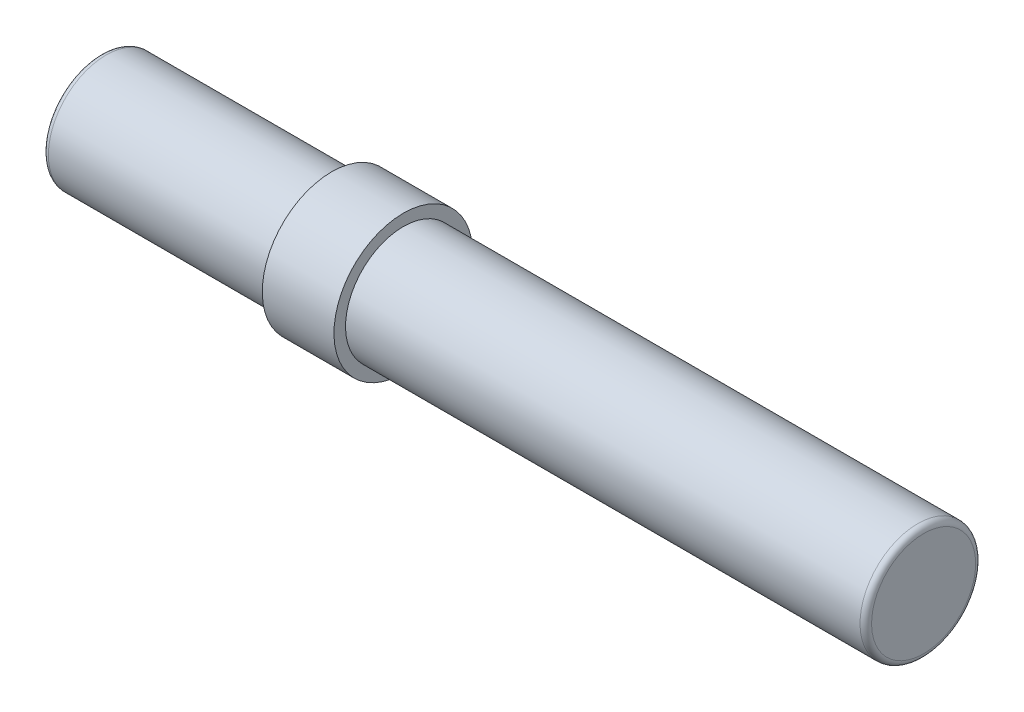
SolidWorks part; units mm, degrees
material "1.5714 (16NiCr4)"
ref_plane "Ebene vorne" through (0, 0, 0) normal (0, 0, 1) x (1, 0, 0)
ref_plane "Ebene oben" through (0, 0, 0) normal (0, 1, 0) x (1, 0, 0)
ref_plane "Ebene rechts" through (0, 0, 0) normal (1, 0, 0) x (0, 0, -1)
sketch "Skizze1" plane through (0, 0, 0) normal (0, 0, 1) x (1, 0, 0)
  line L0 (-47.1143, 0) -> (-47.1143, 5)
  line L1 (-47.1143, 5) -> (-27.1143, 5)
  line L2 (-27.1143, 5) -> (-27.1143, 6)
  line L3 (-27.1143, 6) -> (-20.9143, 6)
  line L4 (-20.9143, 6) -> (-20.9143, 5)
  line L5 (-20.9143, 5) -> (24.0857, 5)
  line L6 (24.0857, 5) -> (24.0857, 0)
  line L7 (24.0857, 0) -> (-47.1143, 0)
  dimension "D1" = 5
  dimension "D2" = 20
  dimension "D3" = 6.2
  dimension "D4" = 6
  dimension "D5" = 5
  dimension "D6" = 45
revolve "Rotation1" add sketch "Skizze1" angle 360 about L7
fillet "Verrundung1" radius 0.5 2 edges at (24.0857, 5, 0) (-47.1143, 5, 0)
